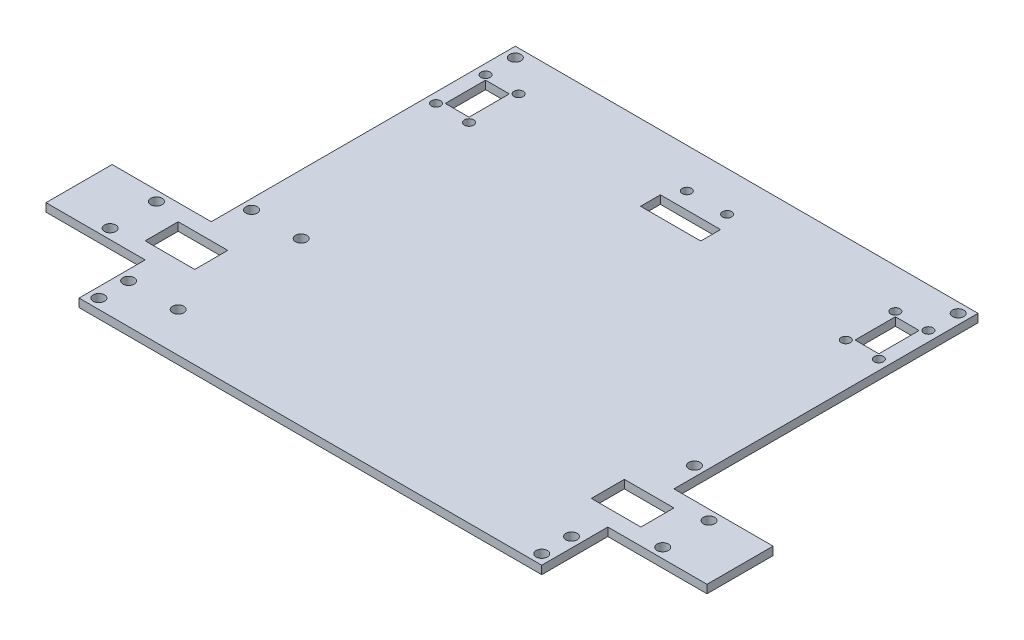
SolidWorks part; units mm, degrees
ref_plane "Front Plane" through (0, 0, 0) normal (0, 0, 1) x (1, 0, 0)
ref_plane "Top Plane" through (0, 0, 0) normal (0, 1, 0) x (1, 0, 0)
ref_plane "Right Plane" through (0, 0, 0) normal (1, 0, 0) x (0, 0, -1)
sketch "Sketch1" plane through (0, 0, 0) normal (0, 1, 0) x (1, 0, 0)
  line L1 (-52.9222, 15.7603) -> (124.8778, 15.7603)
  line L2 (-52.9222, 15.7603) -> (-52.9222, -101.0797)
  line L3 (-52.9222, -151.8797) -> (124.8778, -151.8797)
  line L4 (124.8778, 15.7603) -> (124.8778, -101.0797)
  line L7 (124.8778, -101.0797) -> (162.9778, -101.0797)
  line L8 (162.9778, -126.4797) -> (162.9778, -101.0797)
  line L11 (-52.9222, -101.0797) -> (-91.0222, -101.0797)
  line L12 (-91.0222, -126.4797) -> (-91.0222, -101.0797)
  line L15 (-91.0222, -126.4797) -> (-52.9222, -126.4797)
  line L16 (-52.9222, -151.8797) -> (-52.9222, -126.4797)
  line L19 (162.9778, -126.4797) -> (124.8778, -126.4797)
  line L20 (124.8778, -151.8797) -> (124.8778, -126.4797)
  dimension "D1" = 177.8
  dimension "D2" = 167.64
  dimension "D3" = 38.1
  dimension "D4" = 25.4
  dimension "D5" = 38.1
  dimension "D6" = 25.4
extrude "Boss-Extrude1" add sketch "Sketch1" along normal blind 3.175
sketch "Sketch2" plane through (0, 3.175, 0) normal (0, 1, 0) x (1, 0, 0)
  line L0 (124.8778, 15.7603) -> (-52.9222, 15.7603) construction
  line L1 (-52.9222, 15.7603) -> (-52.9222, -101.0797) construction
  line L2 (124.8778, -101.0797) -> (124.8778, 15.7603) construction
  line L3 (-52.9222, -151.8797) -> (124.8778, -151.8797) construction
  line L4 (-52.9222, -101.0797) -> (-91.0222, -101.0797) construction
  line L5 (-47.3342, -1.2577) -> (-38.1902, -1.2577)
  line L6 (-47.3342, -1.2577) -> (-47.3342, -16.7517)
  line L7 (-47.3342, -16.7517) -> (-38.1902, -16.7517)
  line L8 (-38.1902, -1.2577) -> (-38.1902, -16.7517)
  line L9 (110.1458, -1.2577) -> (119.2898, -1.2577)
  line L10 (110.1458, -1.2577) -> (110.1458, -16.7517)
  line L11 (110.1458, -16.7517) -> (119.2898, -16.7517)
  line L12 (119.2898, -1.2577) -> (119.2898, -16.7517)
  line L13 (24.4208, -5.8297) -> (47.5348, -5.8297)
  line L14 (24.4208, -5.8297) -> (24.4208, -13.4497)
  line L15 (24.4208, -13.4497) -> (47.5348, -13.4497)
  line L16 (47.5348, -5.8297) -> (47.5348, -13.4497)
  line L17 (-91.0222, -101.0797) -> (-91.0222, -126.4797) construction
  line L18 (-91.0222, -126.4797) -> (-52.9222, -126.4797) construction
  line L19 (162.9778, -126.4797) -> (162.9778, -101.0797) construction
  line L20 (124.8778, -126.4797) -> (162.9778, -126.4797) construction
  line L21 (162.9778, -101.0797) -> (124.8778, -101.0797) construction
  line L23 (-59.2722, -107.4297) -> (-40.2222, -107.4297)
  line L24 (-59.2722, -107.4297) -> (-59.2722, -120.1297)
  line L25 (-59.2722, -120.1297) -> (-40.2222, -120.1297)
  line L26 (-40.2222, -107.4297) -> (-40.2222, -120.1297)
  line L27 (131.2278, -107.4297) -> (112.1778, -107.4297)
  line L28 (131.2278, -107.4297) -> (131.2278, -120.1297)
  line L29 (131.2278, -120.1297) -> (112.1778, -120.1297)
  line L30 (112.1778, -107.4297) -> (112.1778, -120.1297)
  circle A0 centre (-49.1122, 11.9503) radius 2.1717
  circle A1 centre (121.0678, 11.9503) radius 2.1717
  circle A2 centre (-49.1122, -148.0697) radius 2.1717
  circle A3 centre (121.0678, -148.0697) radius 2.1717
  circle A4 centre (-49.1122, -136.6397) radius 2.1717
  circle A5 centre (-49.1122, -89.3957) radius 2.1717
  circle A6 centre (-30.0622, -136.6397) radius 2.1717
  circle A7 centre (-30.0622, -89.3957) radius 2.1717
  circle A8 centre (121.0678, -136.6397) radius 2.1717
  circle A9 centre (121.0678, -89.3957) radius 2.1717
  circle A10 centre (-49.1122, 0.5203) radius 1.778
  circle A11 centre (-49.1122, -18.5297) radius 1.778
  circle A12 centre (-36.4122, 0.5203) radius 1.778
  circle A13 centre (-36.4122, -18.5297) radius 1.778
  circle A14 centre (121.0678, 0.5203) radius 1.778
  circle A15 centre (121.0678, -18.5297) radius 1.778
  circle A16 centre (108.3678, 0.5203) radius 1.778
  circle A17 centre (108.3678, -18.5297) radius 1.778
  circle A18 centre (28.2308, 0.5203) radius 1.778
  circle A19 centre (43.7248, 0.5203) radius 1.778
  circle A20 centre (-70.1942, -104.8897) radius 2.1717
  circle A21 centre (-70.1942, -122.6697) radius 2.1717
  circle A22 centre (142.1498, -104.8897) radius 2.1717
  circle A23 centre (142.1498, -122.6697) radius 2.1717
  point P84 (-40.2222, -113.7797)
  dimension "D1" = 3.81
  dimension "D3" = 3.81
  dimension "D5" = 3.81
  dimension "D7" = 3.81
  dimension "D9" = 11.43
  dimension "D11" = 47.244
  dimension "D12" = 19.05
  dimension "D13" = 19.05
  dimension "D17" = 15.24
  dimension "D19" = 3.81
  dimension "D21" = 3.81
  dimension "D22" = 3.81
  dimension "D25" = 12.7
  dimension "D26" = 12.7
  dimension "D28" = 19.05
  dimension "D35" = 15.24
  dimension "D38" = 3.556
  dimension "D53" = 3.81
  dimension "D55" = 3.81
  dimension "D57" = 20.828
  dimension "D58" = 3.81
  dimension "D2" = 3.81
  dimension "D4" = 3.81
  dimension "D6" = 3.81
  dimension "D8" = 3.81
  dimension "D10" = 3.81
  dimension "D14" = 47.244
  dimension "D15" = 15.24
  dimension "D16" = 3.81
  dimension "D18" = 3.81
  dimension "D20" = 47.244
  dimension "D23" = 19.05
  dimension "D24" = 11.43
  dimension "D27" = 19.05
  dimension "D29" = 11.43
  dimension "D30" = 12.7
  dimension "D31" = 12.7
  dimension "D32" = 19.05
  dimension "D33" = 3.81
  dimension "D34" = 3.81
  dimension "D36" = 81.153
  dimension "D37" = 15.494
  dimension "D39" = 15.24
  dimension "D40" = 1.778
  dimension "D41" = 1.778
  dimension "D42" = 1.778
  dimension "D43" = 1.778
  dimension "D44" = 1.778
  dimension "D45" = 1.778
  dimension "D46" = 1.778
  dimension "D47" = 1.778
  dimension "D48" = 1.778
  dimension "D49" = 23.114
  dimension "D50" = 3.81
  dimension "D51" = 6.35
  dimension "D52" = 7.62
  dimension "D54" = 20.828
  dimension "D56" = 20.828
  dimension "D59" = 20.828
  dimension "D60" = 3.81
  dimension "D61" = 19.05
  dimension "D62" = 12.7
  dimension "D63" = 6.35
  dimension "D64" = 12.7
  dimension "D65" = 12.7
  dimension "D66" = 19.05
  dimension "D67" = 12.7
  dimension "D68" = 6.35
extrude "Cut-Extrude1" cut sketch "Sketch2" against normal blind 3.175
